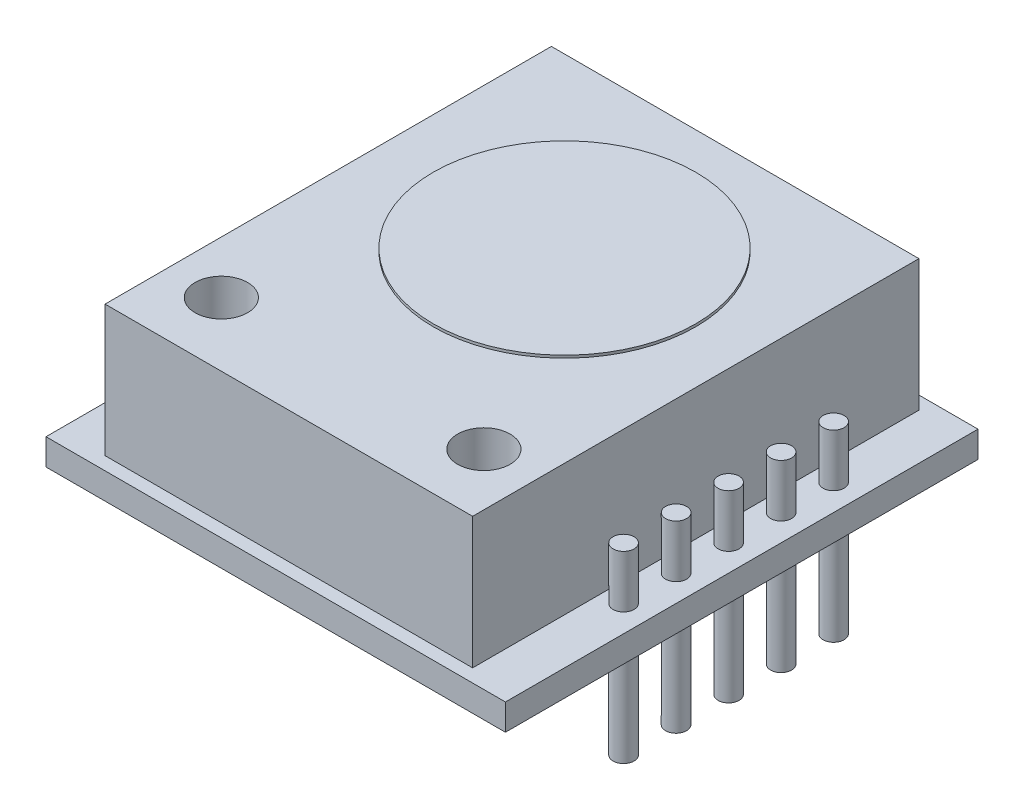
SolidWorks part; units mm, degrees
ref_plane "Спереди" through (0, 0, 0) normal (0, 0, 1) x (1, 0, 0)
ref_plane "Сверху" through (0, 0, 0) normal (0, 1, 0) x (1, 0, 0)
ref_plane "Справа" through (0, 0, 0) normal (1, 0, 0) x (0, 0, -1)
sketch "Sketch1" plane through (0, 0, 0) normal (0, 1, 0) x (1, 0, 0)
  line L1 (-8.75, -9) -> (8.75, -9)
  line L2 (-8.75, -9) -> (-8.75, 9)
  line L3 (-8.75, 9) -> (8.75, 9)
  line L4 (8.75, -9) -> (8.75, 9)
  line L5 (-8.75, -9) -> (8.75, 9) construction
  line L6 (-8.75, 9) -> (8.75, -9) construction
  circle A5 centre (-7.95, -5.1) radius 0.4
  circle A6 centre (-7.95, -3.1) radius 0.4
  circle A7 centre (-7.95, -1.1) radius 0.4
  circle A8 centre (-7.95, 0.9) radius 0.4
  circle A9 centre (-7.95, 2.9) radius 0.4
  circle A10 centre (-7.95, 4.9) radius 0.4
  point P0 (0, 0)
  dimension "D4" = 0.8
  dimension "D3" = 0.8
  dimension "D1" = 17.5
  dimension "D2" = 18
  dimension "D5" = 3.9
  dimension "D6" = 6
extrude "Boss-Extrude1" add sketch "Sketch1" along normal blind 1
sketch "Sketch3" plane through (0, 1, 0) normal (0, 1, 0) x (1, 0, 0)
  line L1 (-7, -8.5) -> (7, -8.5)
  line L2 (-7, -8.5) -> (-7, 8.5)
  line L3 (-7, 8.5) -> (7, 8.5)
  line L4 (7, -8.5) -> (7, 8.5)
  line L5 (-7, -8.5) -> (7, 8.5) construction
  line L6 (-7, 8.5) -> (7, -8.5) construction
  circle A0 centre (-5, -6.0714) radius 1
  circle A1 centre (5, -6.0714) radius 1
  point P0 (0, 0)
  point P10 (0, 0)
  dimension "D5" = 2
  dimension "D6" = 2
  dimension "D1" = 17
  dimension "D2" = 14
  dimension "D3" = 2
  dimension "D4" = 2
extrude "Boss-Extrude2" add sketch "Sketch3" along normal blind 5
sketch "Sketch4" plane through (0, 1, 0) normal (0, 1, 0) x (1, 0, 0)
  line L0 (8.75, -9) -> (8.75, 9) construction
  line L1 (8.75, 9) -> (-8.75, 9) construction
  circle A0 centre (7.75, 4.5) radius 0.4
  circle A1 centre (7.75, 2.5) radius 0.4
  circle A2 centre (7.75, 0.5) radius 0.4
  circle A3 centre (7.75, -1.5) radius 0.4
  circle A4 centre (7.75, -3.5) radius 0.4
  dimension "D1" = 0.8
  dimension "D2" = 1
  dimension "D3" = 4.5
  dimension "D4" = 5
extrude "Boss-Extrude3" add sketch "Sketch4" along normal blind 2 and the other way blind 5
sketch "Sketch5" plane through (0, 6, 0) normal (0, 1, 0) x (1, 0, 0)
  line L0 (0, 10.0823) -> (0, -10.8877) construction
  line L1 (7, 8.5) -> (-7, 8.5) construction
  circle A0 centre (0, 2) radius 5
  point P2 (0, 0)
  dimension "D1" = 10
  dimension "D2" = 6.5
extrude "Boss-Extrude4" add sketch "Sketch5" along normal blind 0.1
